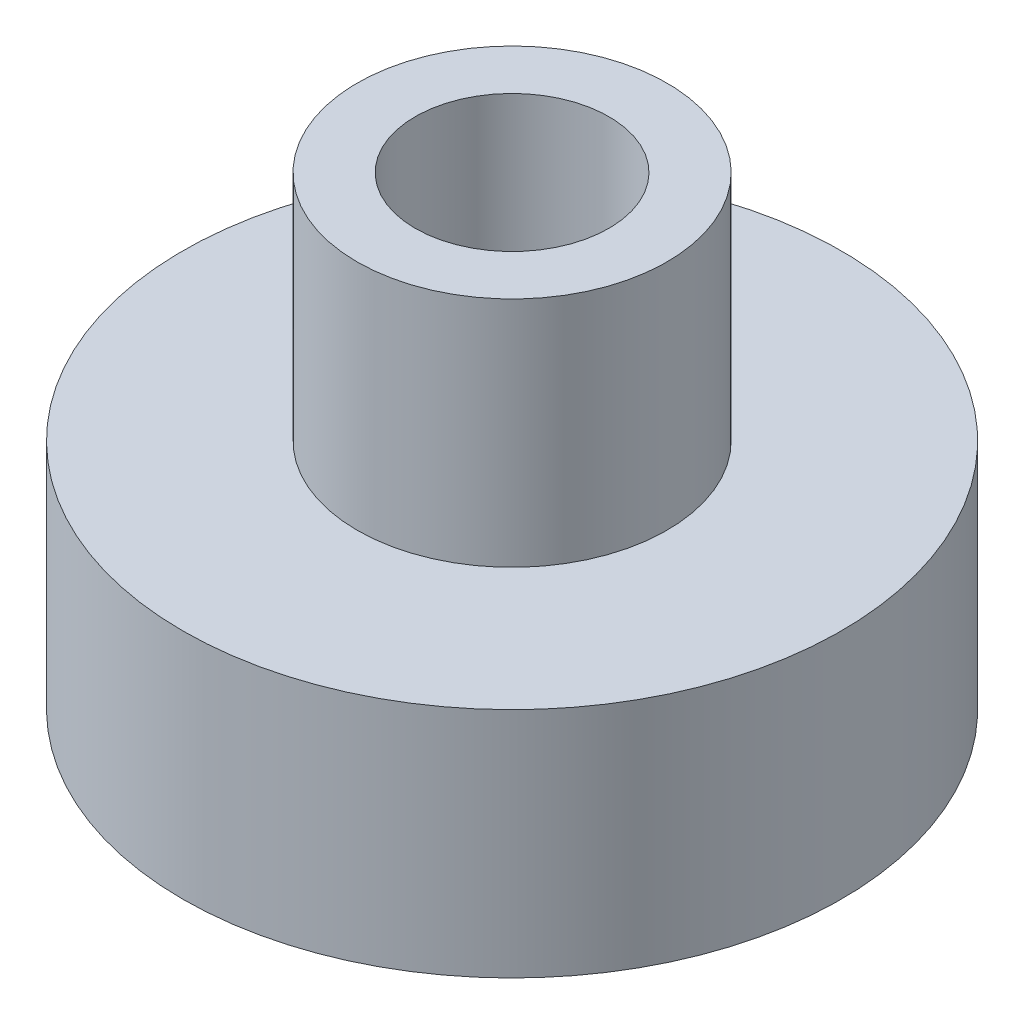
SolidWorks part; units mm, degrees
ref_plane "Plan de face" through (0, 0, 0) normal (0, 0, 1) x (1, 0, 0)
ref_plane "Plan de dessus" through (0, 0, 0) normal (0, 1, 0) x (1, 0, 0)
ref_plane "Plan de droite" through (0, 0, 0) normal (1, 0, 0) x (0, 0, -1)
sketch "Esquisse1" plane through (0, 0, 0) normal (0, 1, 0) x (1, 0, 0)
  circle A0 centre (0, 0) radius 8.5
extrude "Boss.-Extru.1" add sketch "Esquisse1" along normal blind 6
sketch "Esquisse2" plane through (0, 6, 0) normal (0, 1, 0) x (1, 0, 0)
  circle A0 centre (0, 0) radius 4
extrude "Boss.-Extru.2" add sketch "Esquisse2" along normal blind 6
sketch "Esquisse3" plane through (0, 12, 0) normal (0, 1, 0) x (1, 0, 0)
  circle A0 centre (0, 0) radius 2.5
extrude "Enlèv. mat.-Extru.1" cut sketch "Esquisse3" against normal up to next
